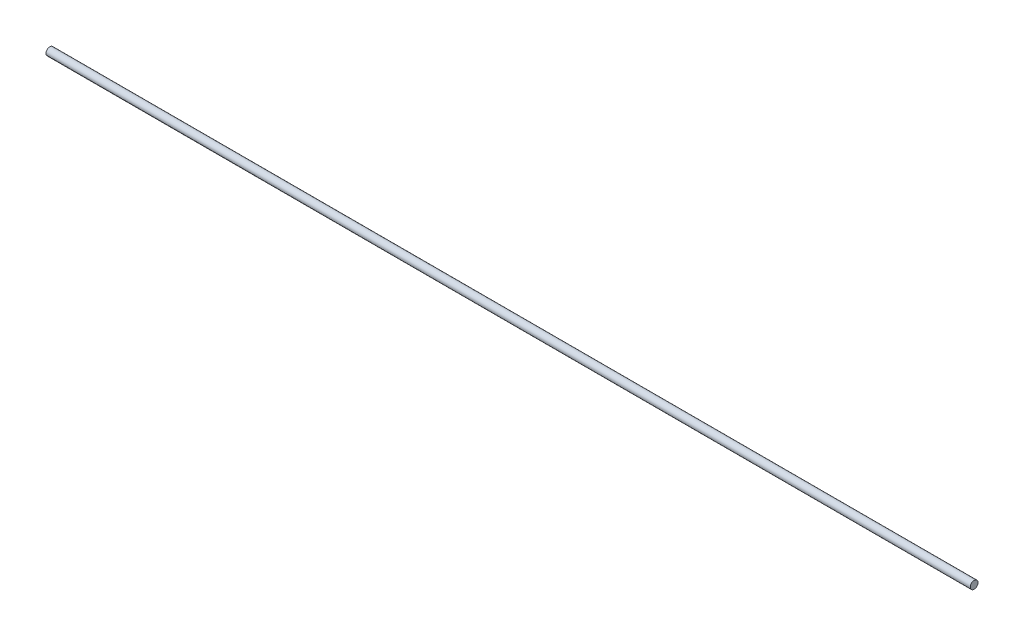
SolidWorks part; units mm, degrees
ref_plane "Front Plane" through (0, 0, 0) normal (0, 0, 1) x (1, 0, 0)
ref_plane "Top Plane" through (0, 0, 0) normal (0, 1, 0) x (1, 0, 0)
ref_plane "Right Plane" through (0, 0, 0) normal (1, 0, 0) x (0, 0, -1)
sketch "Sketch1" plane through (0, 0, 0) normal (0, 1, 0) x (1, 0, 0)
  line L1 (-28.5028, 5.2126) -> (31.4972, 5.2126)
  line L2 (-28.5028, 5.2126) -> (-28.5028, 4.9626)
  line L3 (-28.5028, 4.9626) -> (31.4972, 4.9626)
  line L4 (31.4972, 5.2126) -> (31.4972, 4.9626)
  dimension "D1" = 60
  dimension "D2" = 0.25
revolve "Revolve1" add sketch "Sketch1" angle 360 about L3
